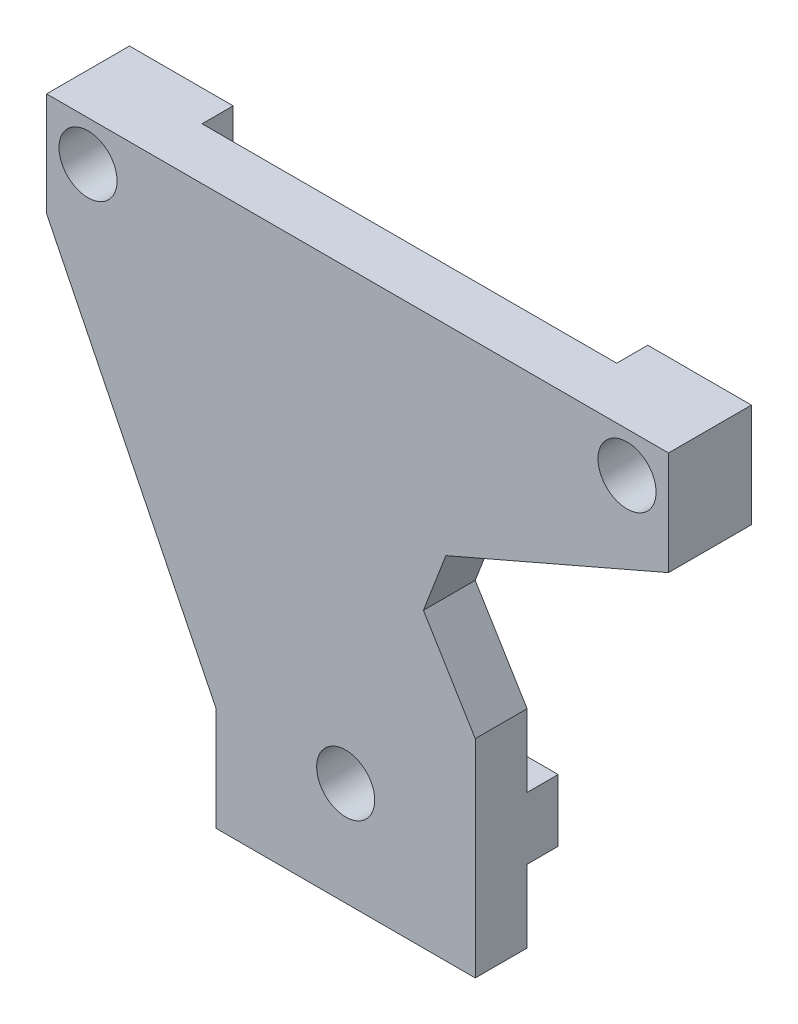
SolidWorks part; units mm, degrees
ref_plane "Plan de face" through (0, 0, 0) normal (0, 0, 1) x (1, 0, 0)
ref_plane "Plan de dessus" through (0, 0, 0) normal (0, 1, 0) x (1, 0, 0)
ref_plane "Plan de droite" through (0, 0, 0) normal (1, 0, 0) x (0, 0, -1)
sketch "Esquisse1" plane through (0, 0, 0) normal (0, 0, 1) x (1, 0, 0)
  line L0 (0, 0) -> (60, 0)
  line L1 (60, 0) -> (60, -10)
  line L2 (0, 0) -> (0, -10)
  line L3 (0, -10) -> (16.3569, -43.1881)
  line L4 (16.3569, -43.1881) -> (16.3569, -53.1881)
  line L5 (16.3569, -53.1881) -> (41.3569, -53.1881)
  line L6 (41.3569, -53.1881) -> (41.3569, -33.1881)
  line L8 (41.3569, -33.1881) -> (36.3557, -24.9678)
  line L9 (36.3557, -24.9678) -> (38.5227, -19.3147)
  line L10 (38.5227, -19.3147) -> (60, -10)
  point P9 (15.4728, -41.3942)
  dimension "D1" = 60
  dimension "D2" = 10
  dimension "D3" = 37
  dimension "D4" = 10
  dimension "D5" = 25
  dimension "D6" = 20
extrude "Boss.-Extru.1" add sketch "Esquisse1" along normal blind 5
sketch "Esquisse2" plane through (0, 0, 0) normal (0, 0, -1) x (-1, 0, 0)
  line L0 (-60, -10) -> (-60, 0) construction
  line L1 (-60, 0) -> (-50, 0)
  line L2 (-60, 0) -> (-60, -10)
  line L3 (-60, -10) -> (-50, -10)
  line L4 (-50, 0) -> (-50, -10)
  line L5 (-60, 0) -> (0, 0) construction
  line L7 (0, 0) -> (-10, 0)
  line L8 (0, 0) -> (0, -10)
  line L9 (0, -10) -> (-10, -10)
  line L10 (-10, 0) -> (-10, -10)
  line L21 (-41.3569, -53.1881) -> (-41.3569, -33.1881) construction
  line L22 (-41.3569, -40.1881) -> (-16.3569, -40.1881)
  line L23 (-41.3569, -40.1881) -> (-41.3569, -46.1881)
  line L24 (-41.3569, -46.1881) -> (-16.3569, -46.1881)
  line L25 (-16.3569, -40.1881) -> (-16.3569, -46.1881)
  line L26 (-16.3569, -43.1881) -> (-16.3569, -53.1881) construction
  line L27 (-16.3569, -53.1881) -> (-41.3569, -53.1881) construction
  point P17 (0, 0)
  point P22 (0, 0)
  point P23 (0, 0)
  dimension "D1" = 10
  dimension "D2" = 10
  dimension "D3" = 10
  dimension "D4" = 6
  dimension "D5" = 7
extrude "Boss.-Extru.2" add sketch "Esquisse2" along normal blind 3 contours L23 L22 L25 L24 | L2 L1 L4 L3 | L8 L7 L10 L9
sketch "Esquisse3" plane through (0, 0, -3) normal (0, 0, -1) x (-1, 0, 0)
  line L0 (-56, -3.88) -> (-4, -3.88) construction
  line L1 (-60, 0) -> (-60, -10) construction
  line L3 (-50, 0) -> (-60, 0) construction
  line L5 (-41.3569, -40.1881) -> (-41.3569, -46.1881) construction
  line L9 (-16.3569, -53.1881) -> (-41.3569, -53.1881) construction
  circle A0 centre (-56, -3.88) radius 2.8
  circle A1 centre (-4, -3.88) radius 2.8
  circle A3 centre (-28.8569, -43.1881) radius 2.8
  dimension "D3" = 5.6
  dimension "D6" = 5.6
  dimension "D1" = 52
  dimension "D2" = 4
  dimension "D4" = 3.88
  dimension "D5" = 12.5
  dimension "D7" = 10
extrude "Enlèv. mat.-Extru.3" cut sketch "Esquisse3" against normal blind 8.1
